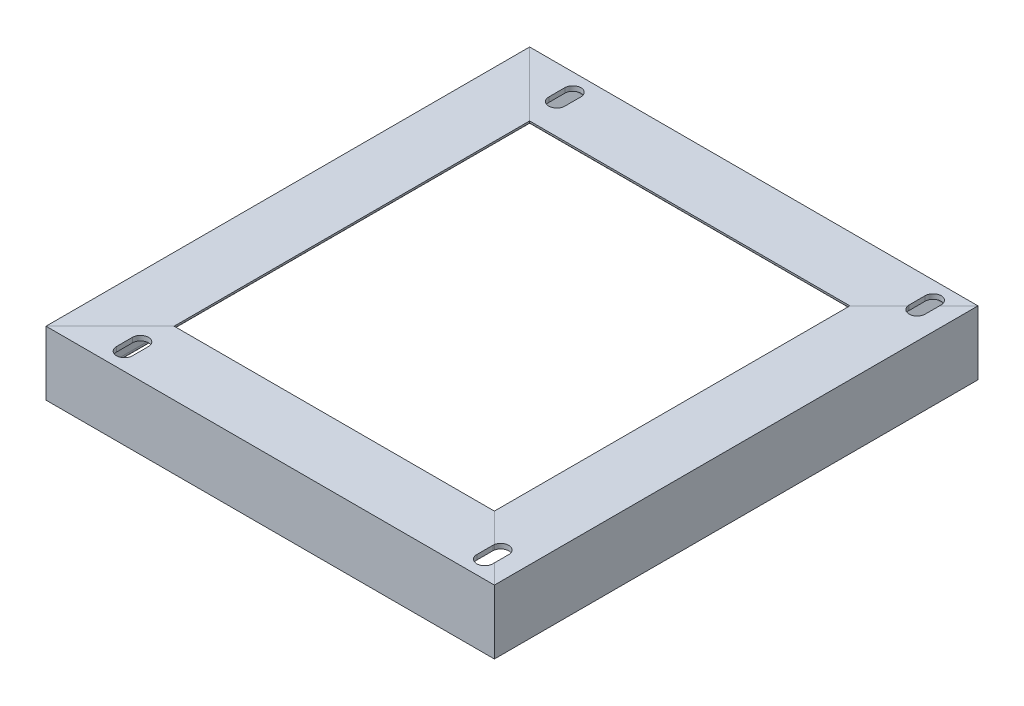
SolidWorks part; units mm, degrees
ref_plane "Front Plane" through (0, 0, 0) normal (0, 0, 1) x (1, 0, 0)
ref_plane "Top Plane" through (0, 0, 0) normal (0, 1, 0) x (1, 0, 0)
ref_plane "Right Plane" through (0, 0, 0) normal (1, 0, 0) x (0, 0, -1)
sketch3d "3DSketch1"
  line L1 (140, 0, 151) -> (140, 0, -151)
  line L2 (140, 0, 151) -> (-140, 0, 151)
  line L3 (-140, 0, 151) -> (-140, 0, -151)
  line L4 (140, 0, -151) -> (-140, 0, -151)
  line L5 (140, 0, 151) -> (-140, 0, -151) construction
  line L6 (-140, 0, 151) -> (140, 0, -151) construction
  point P0 (0, 0, 0)
  dimension "D1" = 302
  dimension "D2" = 280
other "Iron V40X40X3(2)"
ref_plane "Plane2" through (-140, 0, 151) normal (0, 0, -1) x (1, 0, 0)
sketch "Sketch1" plane through (-140, 0, 151) normal (0, 0, -1) x (1, 0, 0)
  line L0 (0, 0) -> (0, 40)
  line L1 (0, 20) -> (3, 20) construction
  line L2 (3, 37) -> (3, 6.5)
  line L3 (6.5, 3) -> (37, 3)
  line L4 (20, 3) -> (20, 0) construction
  line L5 (40, 0) -> (0, 0)
  arc A0 (40, 0) -> (37, 3) centre (37, 0) ccw
  arc A1 (0, 40) -> (3, 37) centre (0, 37) cw
  arc A2 (6.5, 3) -> (3, 6.5) centre (6.5, 6.5) cw
  point P10 (20, 0)
  point P14 (0, 20)
  point P15 (3, 20)
  point P16 (20, 3)
  point P17 (3, 40)
  point P18 (40, 3)
  point P21 (0, 0)
  dimension "D2" = 3
  dimension "D3" = 40
  dimension "Radius_1" = 3.5
  dimension "D1" = 3
sketch "Sketch2" plane through (0, 0, 0) normal (0, 1, 0) x (1, 0, 0)
  line L0 (-102, 140) -> (-102, 130) construction
  line L1 (-97, 140) -> (-97, 130)
  line L2 (-107, 140) -> (-107, 130)
  line L3 (-140, 151) -> (-140, -151) construction
  line L4 (140, 151) -> (-140, 151) construction
  line L5 (123, 140) -> (123, 130) construction
  line L6 (128, 140) -> (128, 130)
  line L7 (118, 140) -> (118, 130)
  line L8 (123, -130) -> (123, -140) construction
  line L9 (128, -130) -> (128, -140)
  line L10 (118, -130) -> (118, -140)
  line L11 (-102, -130) -> (-102, -140) construction
  line L12 (-97, -130) -> (-97, -140)
  line L13 (-107, -130) -> (-107, -140)
  arc A0 (-97, 140) -> (-107, 140) centre (-102, 140) ccw
  arc A1 (-107, 130) -> (-97, 130) centre (-102, 130) ccw
  arc A2 (128, 140) -> (118, 140) centre (123, 140) ccw
  arc A3 (118, 130) -> (128, 130) centre (123, 130) ccw
  arc A4 (128, -130) -> (118, -130) centre (123, -130) ccw
  arc A5 (118, -140) -> (128, -140) centre (123, -140) ccw
  arc A6 (-97, -130) -> (-107, -130) centre (-102, -130) ccw
  arc A7 (-107, -140) -> (-97, -140) centre (-102, -140) ccw
  point P2 (-102, 135)
  point P16 (123, 135)
  point P23 (123, -135)
  point P30 (-102, -135)
  dimension "D2" = 5
  dimension "D4" = 11
  dimension "D1" = 10
  dimension "D3" = 38
  dimension "D5" = 2
  dimension "D6" = 2
extrude "Cut-Extrude2" cut sketch "Sketch2" against normal blind 20 from offset 10
